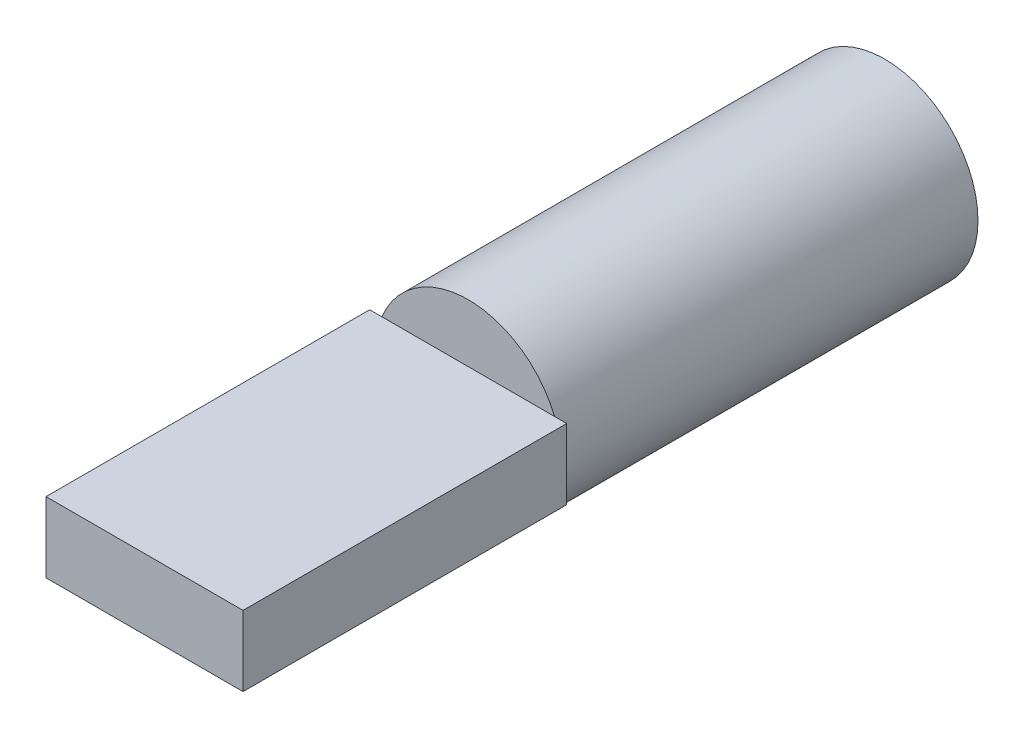
SolidWorks part; units mm, degrees
ref_plane "Front" through (0, 0, 0) normal (0, 0, 1) x (1, 0, 0)
ref_plane "Top" through (0, 0, 0) normal (0, 1, 0) x (1, 0, 0)
ref_plane "Right" through (0, 0, 0) normal (1, 0, 0) x (0, 0, -1)
sketch "Sketch1" plane through (0, 0, 0) normal (0, 0, 1) x (1, 0, 0)
  circle A0 centre (0, 0) radius 6.625
  dimension "D1" = 13.25
extrude "Boss-Extrude1" add sketch "Sketch1" along normal blind 29.6
sketch "Sketch2" plane through (0, 0, 29.6) normal (0, 0, 1) x (1, 0, 0)
  line L1 (-7, -2.5) -> (7, -2.5)
  line L2 (-7, -2.5) -> (-7, 2.5)
  line L3 (-7, 2.5) -> (7, 2.5)
  line L4 (7, -2.5) -> (7, 2.5)
  line L5 (-7, -2.5) -> (7, 2.5) construction
  line L6 (-7, 2.5) -> (7, -2.5) construction
  point P0 (0, 0)
  dimension "D1" = 14
  dimension "D2" = 5
extrude "Boss-Extrude2" add sketch "Sketch2" along normal blind 23
